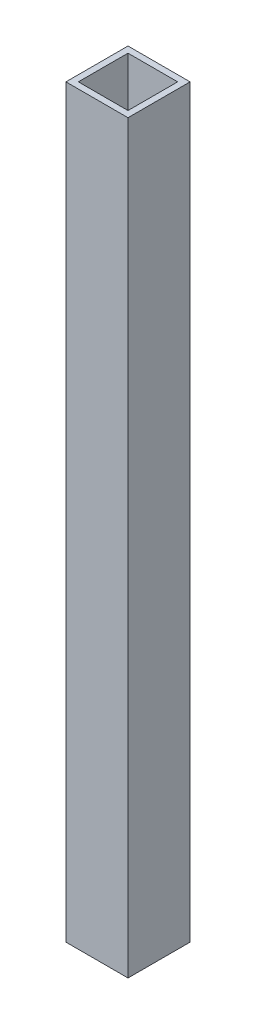
SolidWorks part; units mm, degrees
ref_plane "Front Plane" through (0, 0, 0) normal (0, 0, 1) x (1, 0, 0)
ref_plane "Top Plane" through (0, 0, 0) normal (0, 1, 0) x (1, 0, 0)
ref_plane "Right Plane" through (0, 0, 0) normal (1, 0, 0) x (0, 0, -1)
sketch "Sketch1" plane through (0, 0, 0) normal (0, 1, 0) x (1, 0, 0)
  line L0 (-8, 8) -> (8, 8)
  line L1 (-10, -10) -> (10, -10)
  line L2 (-10, -10) -> (-10, 10)
  line L3 (-10, 10) -> (10, 10)
  line L4 (10, -10) -> (10, 10)
  line L5 (-10, -10) -> (10, 10) construction
  line L6 (-10, 10) -> (10, -10) construction
  line L7 (8, -8) -> (8, 8)
  line L8 (-8, -8) -> (8, -8)
  line L9 (-8, -8) -> (-8, 8)
  point P0 (0, 0)
  dimension "D1" = 20
  dimension "D2" = 2
extrude "Boss-Extrude1" add sketch "Sketch1" along normal blind 240
